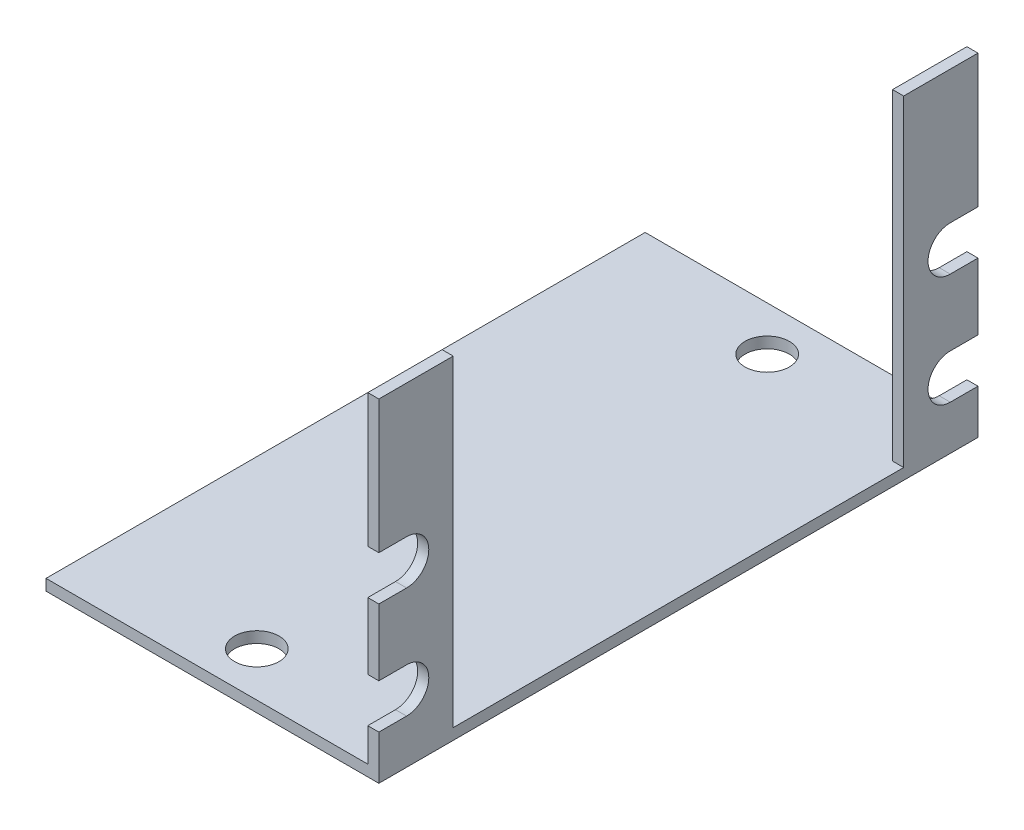
SolidWorks part; units mm, degrees
ref_plane "Front Plane" through (0, 0, 0) normal (0, 0, 1) x (1, 0, 0)
ref_plane "Top Plane" through (0, 0, 0) normal (0, 1, 0) x (1, 0, 0)
ref_plane "Right Plane" through (0, 0, 0) normal (1, 0, 0) x (0, 0, -1)
sketch "Sketch1" plane through (0, 0, 0) normal (0, 0, 1) x (1, 0, 0)
  line L0 (-29, 0) -> (0, 0)
  line L1 (0, 0) -> (0, 29)
  line L2 (0, 29) -> (1, 29)
  line L3 (1, 29) -> (1, -1)
  line L4 (1, -1) -> (-29, -1)
  line L5 (-29, -1) -> (-29, 0)
  dimension "D1" = 30
  dimension "D2" = 1
extrude "Boss-Extrude1" add sketch "Sketch1" along normal mid plane 54
sketch "Sketch2" plane through (0, 0, 0) normal (-1, 0, 0) x (0, 0, 1)
  line L0 (-24.5, 17) -> (-27, 17)
  line L1 (-20.3, 30) -> (20.3, 30)
  line L2 (-20.3, 30) -> (-20.3, 0)
  line L3 (-20.3, 0) -> (20.3, 0)
  line L4 (20.3, 30) -> (20.3, 0)
  line L5 (27, 0) -> (-27, 0) construction
  line L6 (-24.5, 15) -> (-24.5, 5) construction
  line L7 (-19, 10) -> (-24.5, 10) construction
  line L8 (-27, 29) -> (-27, 0) construction
  line L9 (-24.5, 13) -> (-27, 13)
  line L10 (-24.5, 3) -> (-27, 3)
  line L11 (24.5, 7) -> (27, 7)
  line L12 (27, -1) -> (27, 29) construction
  line L13 (24.5, 3) -> (27, 3)
  line L14 (24.5, 13) -> (27, 13)
  line L15 (24.5, 17) -> (27, 17)
  line L16 (-24.5, 7) -> (-27, 7)
  line L17 (-27, -1) -> (-27, 29) construction
  line L20 (27, 17) -> (27, 13)
  line L21 (27, 7) -> (27, 3)
  line L22 (-27, 3) -> (-27, 7)
  line L23 (-27, 13) -> (-27, 17)
  arc A0 (24.5, 17) -> (24.5, 13) centre (24.5, 15) ccw
  arc A1 (24.5, 7) -> (24.5, 3) centre (24.5, 5) ccw
  arc A2 (-24.5, 13) -> (-24.5, 17) centre (-24.5, 15) ccw
  arc A3 (-24.5, 3) -> (-24.5, 7) centre (-24.5, 5) ccw
  dimension "D2" = 4
  dimension "D3" = 10
  dimension "D5" = 49
  dimension "D6" = 24.5
  dimension "D1" = 40.6
  dimension "D4" = 30
  dimension "D7" = 15
extrude "Cut-Extrude1" cut sketch "Sketch2" against normal through all
sketch "Sketch3" plane through (0, 0, 0) normal (0, 1, 0) x (1, 0, 0)
  line L2 (-14, 30.5) -> (-14, -30.5) construction
  line L5 (1, 20.3) -> (1, -20.3) construction
  arc A0 (-16, 23) -> (-12, 23) centre (-14, 23) ccw
  arc A1 (-12, -23) -> (-16, -23) centre (-14, -23) ccw
  arc A2 (-12, 23) -> (-16, 23) centre (-14, 23) ccw
  arc A3 (-12, -23) -> (-16, -23) centre (-14, -23) cw
  dimension "D1" = 4
  dimension "D2" = 46
  dimension "D3" = 23
  dimension "D5" = 2
  dimension "D6" = 2
  dimension "D4" = 15
extrude "Cut-Extrude2" cut sketch "Sketch3" against normal through all
